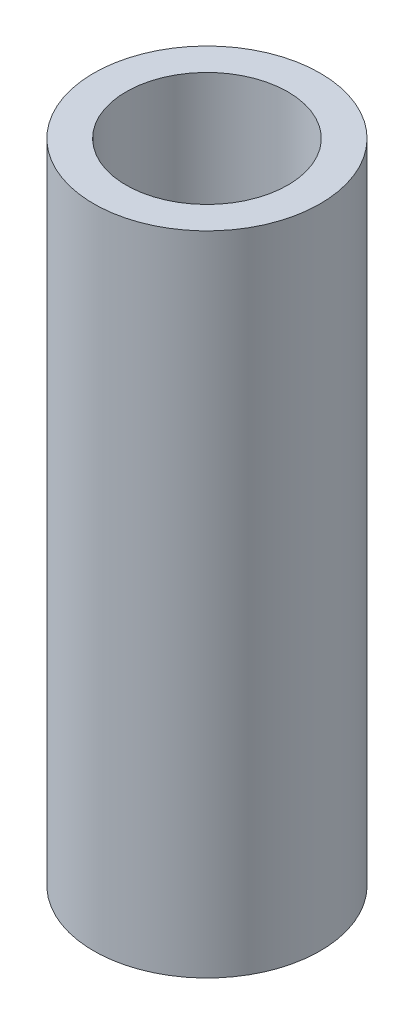
SolidWorks part; units mm, degrees
ref_plane "Front Plane" through (0, 0, 0) normal (0, 0, 1) x (1, 0, 0)
ref_plane "Top Plane" through (0, 0, 0) normal (0, 1, 0) x (1, 0, 0)
ref_plane "Right Plane" through (0, 0, 0) normal (1, 0, 0) x (0, 0, -1)
sketch "Sketch1" plane through (0, 0, 0) normal (0, 0, 1) x (1, 0, 0)
  line L0 (0, 0) -> (0, 16.0594) construction
  line L2 (3.175, 0) -> (4.445, 0)
  line L3 (3.175, 0) -> (3.175, 25.4)
  line L4 (3.175, 25.4) -> (4.445, 25.4)
  line L5 (4.445, 0) -> (4.445, 25.4)
  dimension "D1" = 8.89
  dimension "D2" = 6.35
  dimension "D3" = 25.4
revolve "Revolve1" add sketch "Sketch1" angle 360 about L0
